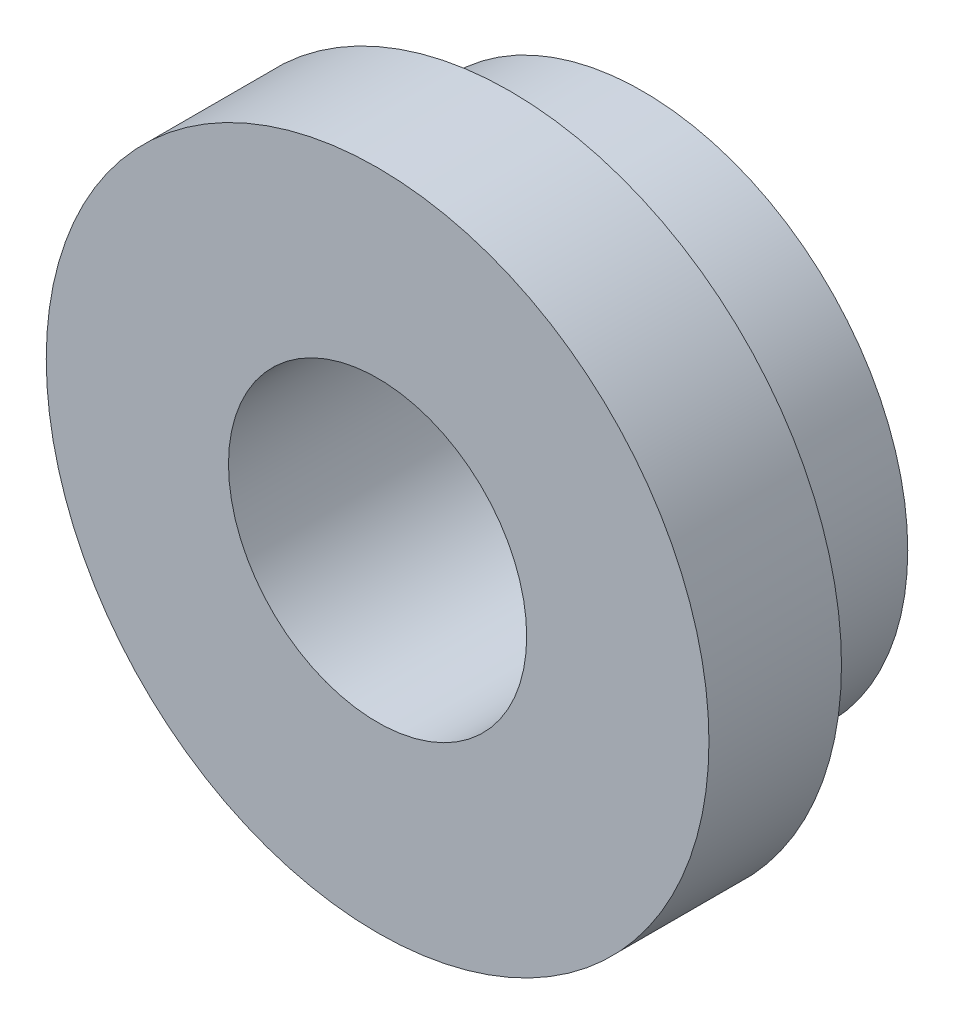
SolidWorks part; units mm, degrees
ref_plane "Front Plane" through (0, 0, 0) normal (0, 0, 1) x (1, 0, 0)
ref_plane "Top Plane" through (0, 0, 0) normal (0, 1, 0) x (1, 0, 0)
ref_plane "Right Plane" through (0, 0, 0) normal (1, 0, 0) x (0, 0, -1)
sketch "Sketch1" plane through (0, 0, 0) normal (0, 0, 1) x (1, 0, 0)
  circle A0 centre (0, 0) radius 4
  circle A1 centre (0, 0) radius 2.25
  dimension "D1" = 8
  dimension "D2" = 4.5
extrude "Boss-Extrude1" add sketch "Sketch1" along normal blind 2
sketch "Sketch2" plane through (0, 0, 2) normal (0, 0, 1) x (1, 0, 0)
  circle A0 centre (0, 0) radius 2.25
  circle A1 centre (0, 0) radius 5
  dimension "D1" = 4.5
  dimension "D2" = 10
extrude "Boss-Extrude2" add sketch "Sketch2" along normal blind 2
